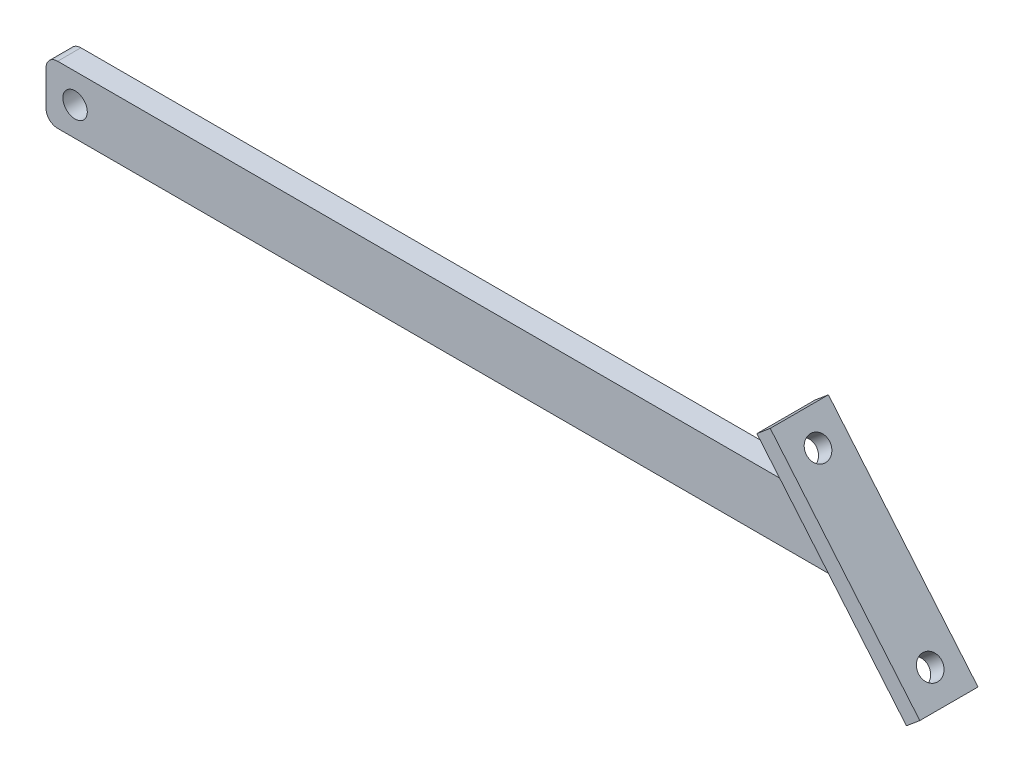
SolidWorks part; units mm, degrees
ref_plane "前视基准面" through (0, 0, 0) normal (0, 0, 1) x (1, 0, 0)
ref_plane "上视基准面" through (0, 0, 0) normal (0, 1, 0) x (1, 0, 0)
ref_plane "右视基准面" through (0, 0, 0) normal (1, 0, 0) x (0, 0, -1)
sketch "草图1" plane through (0, 0, 0) normal (0, 0, 1) x (1, 0, 0)
  line L0 (125.1657, -4.7238) -> (116.7747, 5.2762)
  line L1 (-14.8343, 5.2762) -> (116.7747, 5.2762)
  line L2 (-14.8343, 5.2762) -> (-14.8343, -4.7238)
  line L3 (-14.8343, -4.7238) -> (125.1657, -4.7238)
  circle A0 centre (-9.8343, 0.2762) radius 2.1
  dimension "D5" = 4.2
  dimension "D1" = 10
  dimension "D2" = 140
  dimension "D3" = 5
  dimension "D4" = 5
  dimension "D6" = 50
extrude "凸台-拉伸1" add sketch "草图1" along normal blind 4
fillet "圆角1" radius 2 2 edges at (-14.8343, -4.7238, 2) (-14.8343, 5.2762, 2)
sketch "草图2" plane through (71.1243, 59.6804, 0) normal (0.766, 0.6428, 0) x (0, 0, -1)
  line L0 (-4, -71.0195) -> (-4, 12.2915) construction
  line L1 (-4, -61.0195) -> (3, -61.0195)
  line L2 (0, -84.0736) -> (0, -71.0195) construction
  line L3 (-7, -101.0195) -> (3, -101.0195)
  line L4 (3, -61.0195) -> (3, -101.0195)
  line L5 (-4, -71.0195) -> (0, -71.0195) construction
  line L6 (-4, -84.0736) -> (-4, -71.0195) construction
  line L7 (-4, -61.0195) -> (-7, -61.0195)
  line L10 (-7, -61.0195) -> (-7, -101.0195)
  circle A0 centre (-2, -66.0195) radius 2
  circle A1 centre (-2, -96.0195) radius 2
  point P8 (-2, -71.0195)
  dimension "D4" = 4
  dimension "D7" = 4
  dimension "D1" = 40
  dimension "D2" = 3
  dimension "D3" = 10
  dimension "D5" = 5
  dimension "D6" = 5
  dimension "D8" = 3
  dimension "D9" = 5
extrude "凸台-拉伸2" add sketch "草图2" along normal blind 3
